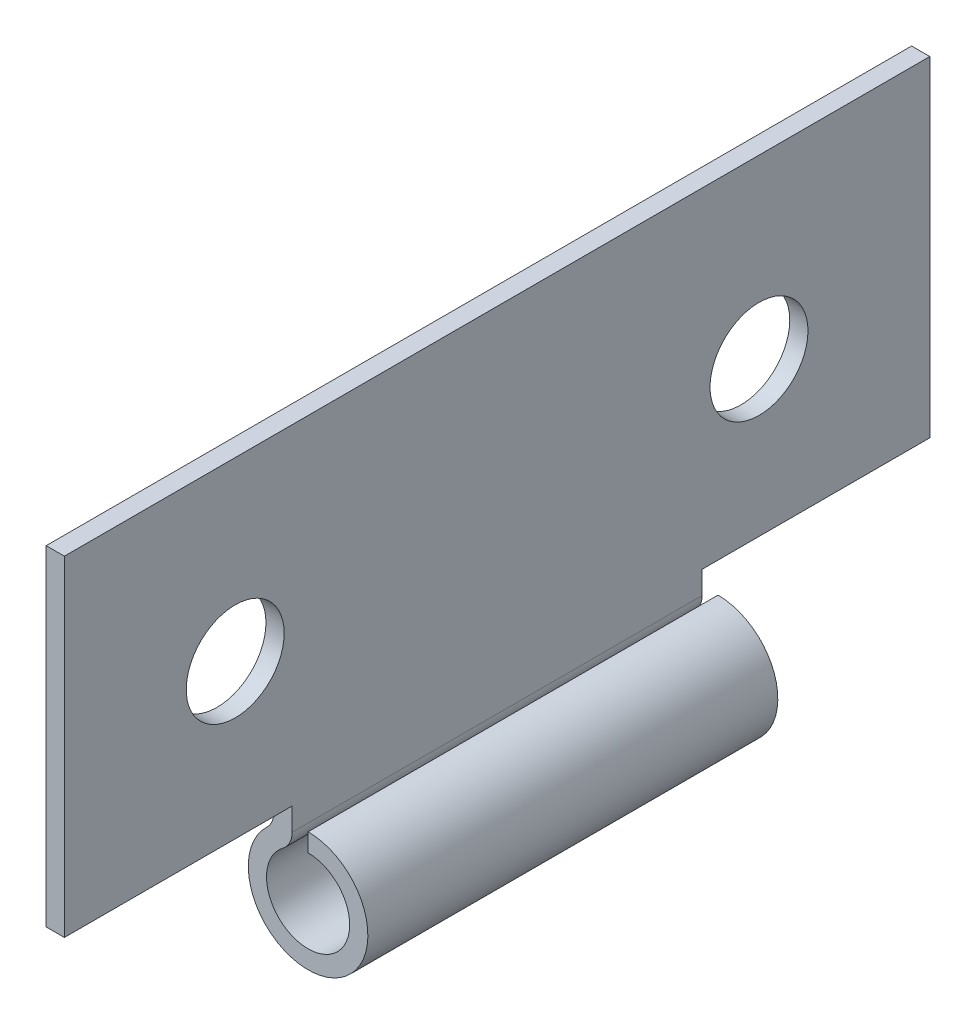
SolidWorks part; units mm, degrees
ref_plane "Front Plane" through (0, 0, 0) normal (0, 0, 1) x (1, 0, 0)
ref_plane "Top Plane" through (0, 0, 0) normal (0, 1, 0) x (1, 0, 0)
ref_plane "Right Plane" through (0, 0, 0) normal (1, 0, 0) x (0, 0, -1)
sketch "Sketch1" plane through (0, 0, 0) normal (0, 0, 1) x (1, 0, 0)
  line L1 (0.8, -0.3688) -> (0.8, 15.1312)
  line L2 (0, 0) -> (0, 15.1312)
  line L3 (0, 15.1312) -> (0.8, 15.1312)
  line L4 (0, 0) -> (1.5, 0) construction
  line L5 (1.5, 0) -> (1.5, -2.625) construction
  line L6 (1.5, 0) -> (1.5, -0.8)
  arc A0 (-0.3103, -0.7241) -> (1.5, 0) centre (1.5, -2.625) ccw
  arc A1 (0.4018, -1.1674) -> (1.5, -0.8) centre (1.5, -2.625) ccw
  arc A2 (0, 0) -> (-0.3103, -0.7241) centre (-1, 0) cw
  circle A3 centre (1.5, -2.625) radius 2.625 construction
  circle A4 centre (1.5, -2.625) radius 1.825 construction
  arc A5 (0.4018, -1.1674) -> (0.8, -0.3688) centre (-0.2, -0.3688) ccw
  point P7 (3.325, -2.625)
  point P15 (4.0103, -1.8575)
  dimension "D2" = 1
  dimension "D3" = 1
  dimension "D1" = 0.8
extrude "Boss-Extrude1" add sketch "Sketch1" along normal blind 38
sketch "Sketch2" plane through (0.8, 0, 0) normal (1, 0, 0) x (0, 0, -1)
  line L0 (-38, 7.3812) -> (0, 7.3812) construction
  line L1 (-38, -0.3688) -> (-38, 15.1312) construction
  line L2 (0, -0.3688) -> (0, 15.1312) construction
  line L3 (-30.5, 9.5312) -> (-0.6946, 9.5312) construction
  circle A0 centre (-30.5, 7.3812) radius 2.15
  circle A1 centre (-7.5, 7.3812) radius 2.15
  dimension "D1" = 4.3
  dimension "D3" = 7.5
  dimension "D2" = 7.5
extrude "Cut-Extrude1" cut sketch "Sketch2" against normal up to next
sketch "Sketch3" plane through (0.8, 0, 0) normal (1, 0, 0) x (0, 0, -1)
  line L0 (-19, 15.1312) -> (-19, 0.6312) construction
  line L1 (-38, 15.1312) -> (0, 15.1312) construction
  line L2 (-10, 0.6312) -> (0, 0.6312)
  line L6 (-28, 0.6312) -> (-28, -5.25)
  line L8 (-28, 0.6312) -> (-28, -5.25)
  line L10 (-10, 0.6312) -> (-10, -5.25)
  line L12 (-10, 0.6312) -> (-10, -5.25)
  line L13 (0, -0.3688) -> (0, 15.1312) construction
  line L14 (0, 0.6312) -> (0, -5.25)
  line L15 (0, -5.25) -> (-10, -5.25)
  line L16 (-28, -5.25) -> (-38, -5.25)
  line L17 (-38, -5.25) -> (-38, 0.6312)
  line L18 (-38, -0.3688) -> (-38, 15.1312) construction
  line L19 (-38, 0.6312) -> (-28, 0.6312)
  line M4 (0, -0.3688) -> (0, 15.1312)
  line M6 (-38, 15.1312) -> (-38, -0.3688)
  line M7 (-38, -0.3688) -> (0, -0.3688)
extrude "Cut-Extrude4" cut sketch "Sketch3" against normal through all both and the other way through all contours L19 L6 M6 M7 | L17 L16 L6 M7 | L2 L10 M7 M4 | L15 L14 L10 M7
